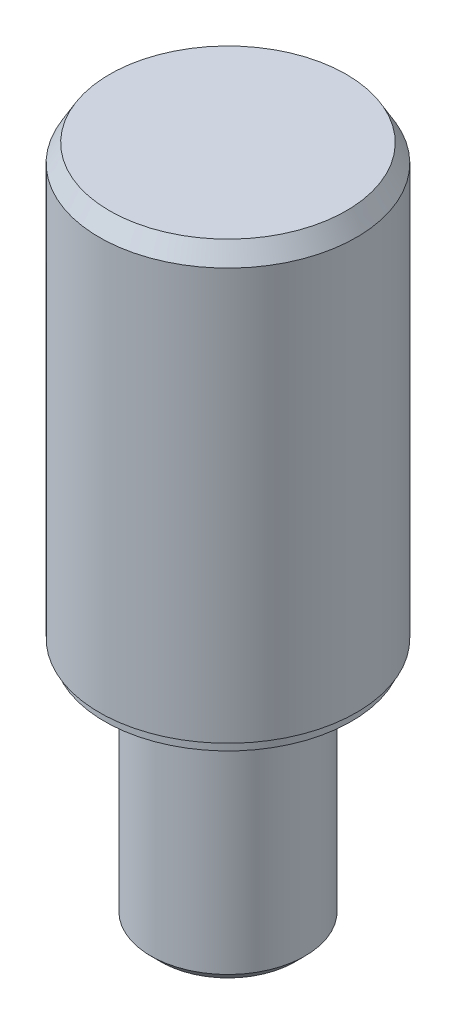
SolidWorks part; units mm, degrees
ref_plane "前视基准面" through (0, 0, 0) normal (0, 0, 1) x (1, 0, 0)
ref_plane "上视基准面" through (0, 0, 0) normal (0, 1, 0) x (1, 0, 0)
ref_plane "右视基准面" through (0, 0, 0) normal (1, 0, 0) x (0, 0, -1)
sketch "草图1" plane through (0, 0, 0) normal (0, 0, 1) x (1, 0, 0)
  line L0 (0, 0) -> (0, 42)
  line L1 (0, 42) -> (11.5, 42)
  line L2 (11.5, 42) -> (12.5, 40.2679)
  line L3 (12.5, 40.2679) -> (12.5, 0.2679)
  line L4 (12.5, 0.2679) -> (12, 0.2679)
  line L5 (12, 0.2679) -> (12, -0.7321)
  line L6 (12, -0.7321) -> (7.5, -0.7321)
  line L7 (7.5, -0.7321) -> (7.5, -22.7321)
  line L8 (6.5, -23.7321) -> (0, -23.7321)
  line L9 (0, -23.7321) -> (0, 0)
  line L10 (7.5, -22.7321) -> (6.5, -23.7321)
  point P9 (7.5, -23.7321)
  dimension "D1" = 42
  dimension "D2" = 11.5
  dimension "D3" = 120
  dimension "D4" = 12.5
  dimension "D5" = 40
  dimension "D7" = 1
  dimension "D8" = 23
revolve "旋转1" add sketch "草图1" angle 360 about L0
